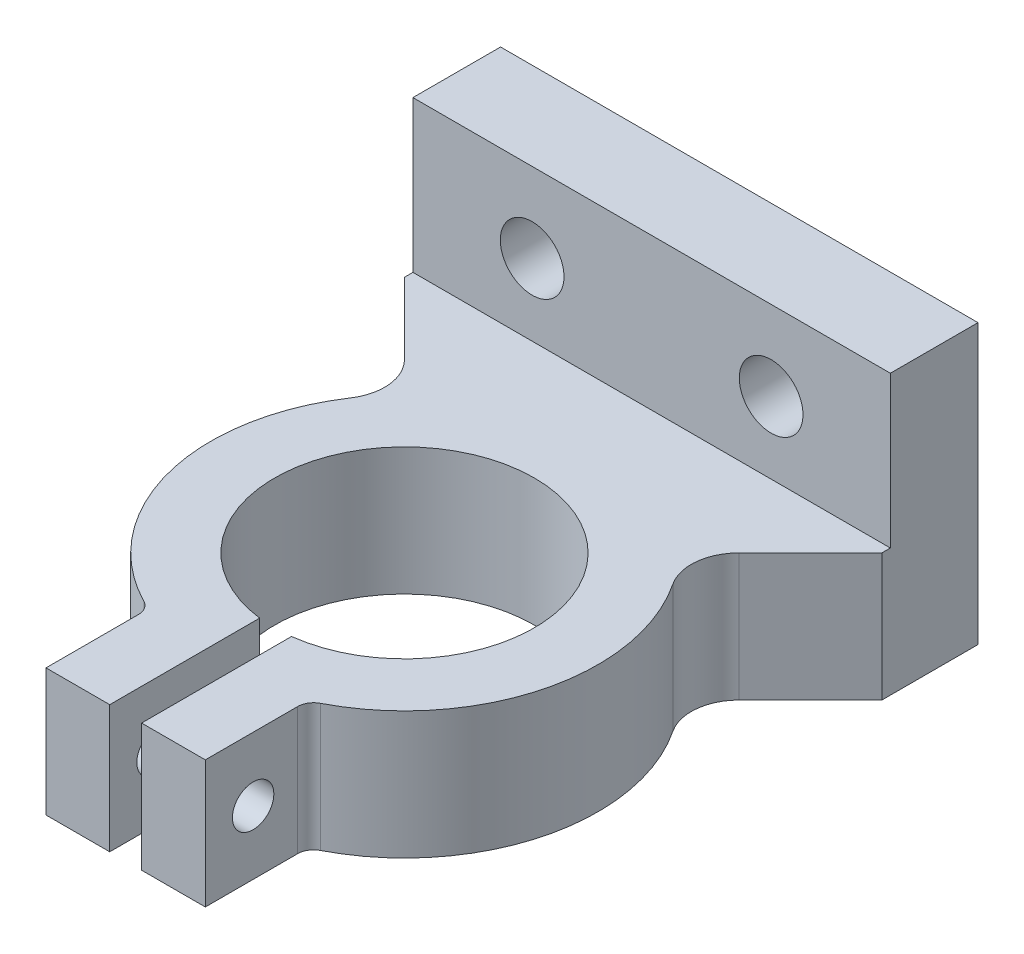
SolidWorks part; units mm, degrees
ref_plane "Front Plane" through (0, 0, 0) normal (0, 0, 1) x (1, 0, 0)
ref_plane "Top Plane" through (0, 0, 0) normal (0, 1, 0) x (1, 0, 0)
ref_plane "Right Plane" through (0, 0, 0) normal (1, 0, 0) x (0, 0, -1)
sketch "Sketch1" plane through (0, 0, 0) normal (0, 1, 0) x (1, 0, 0)
  line L0 (-28.2843, 0) -> (0, 28.2843) construction
  line L1 (-28.2843, 0) -> (0, -28.2843) construction
  line L2 (0, 28.2843) -> (28.2843, 0) construction
  line L3 (0, -28.2843) -> (28.2843, 0) construction
  line L4 (-28.2843, 0) -> (28.2843, 0) construction
  line L5 (0, 28.2843) -> (0, -28.2843) construction
  line L6 (-28.6378, -0.3536) -> (0, -28.9914)
  line L7 (0, -28.9914) -> (28.6378, -0.3536)
  point P1 (0, 0)
  dimension "D1" = 40
  dimension "D2" = 0.5
extrude "Extrude-Thin1" add sketch "Sketch1" along normal blind 60 thin contours L6 L7
sketch "Sketch2" plane through (0, 0, 0) normal (0, 1, 0) x (1, 0, 0)
  line L0 (-31.4663, -3.182) -> (-31.4663, -88)
  line L1 (-31.4663, -88) -> (-2, -88)
  line L2 (31.4663, -88) -> (31.4663, -3.182)
  line L3 (-31.4663, -3.182) -> (0, -34.6482) construction
  line L4 (0, -34.6482) -> (31.4663, -3.182) construction
  line L5 (-31.4663, -3.182) -> (0, -34.6482)
  line L6 (0, -34.6482) -> (31.4663, -3.182)
  line L7 (0, -70) -> (0, -78.5884) construction
  line L8 (-2, -69.1768) -> (-2, -88)
  line L9 (0, -53) -> (0, -34.6482) construction
  line L11 (2, -69.1768) -> (2, -88)
  line L12 (-2, -69.1768) -> (2, -88) construction
  line L13 (-2, -88) -> (2, -69.1768) construction
  line L14 (2, -88) -> (31.4663, -88)
  arc A1 (2, -69.1768) -> (-2, -69.1768) centre (0, -53) ccw
  dimension "D4" = 16.3
  dimension "D1" = 88
  dimension "D2" = 4
  dimension "D3" = 35
extrude "Boss-Extrude1" add sketch "Sketch2" along normal blind 16
sketch "Sketch3" plane through (17.3241, 0, 17.3241) normal (0.7071, 0, 0.7071) x (0.7071, 0, -0.7071)
  line L0 (0, 50) -> (0, 20) construction
  line L1 (2.75, 50) -> (2.75, 20)
  line L2 (-2.75, 50) -> (-2.75, 20)
  arc A0 (2.75, 50) -> (-2.75, 50) centre (0, 50) ccw
  arc A1 (-2.75, 20) -> (2.75, 20) centre (0, 20) ccw
  point P3 (0, 35)
  dimension "D3" = 2.75
  dimension "D1" = 20
  dimension "D2" = 30
extrude "Cut-Extrude1" cut sketch "Sketch3" against normal through all
mirror "Mirror1" about plane through (0, 0, 0) normal (1, 0, 0) of "Cut-Extrude1"
sketch "Sketch5" plane through (0, 0, 0) normal (0, 1, 0) x (1, 0, 0)
  line L0 (-31.4663, -21.5337) -> (-17.1827, -35.8173)
  line L1 (-31.4663, -3.182) -> (-31.4663, -88) construction
  line L2 (-10, -75.147) -> (-10, -88)
  line L3 (-31.4663, -88) -> (-2, -88) construction
  line L4 (-31.4663, -3.182) -> (0, -34.6482) construction
  line L5 (-2, -88) -> (-2, -69.1768) construction
  line L6 (-10, -88) -> (-31.4663, -88)
  line L7 (-31.4663, -88) -> (-31.4663, -21.5337)
  arc A0 (-17.1827, -35.8173) -> (-10, -75.147) centre (0, -53) ccw
  arc A1 (2, -69.1768) -> (-2, -69.1768) centre (0, -53) ccw construction
  dimension "D1" = 8
  dimension "D2" = 8
extrude "Cut-Extrude2" cut sketch "Sketch5" along normal through all
mirror "Mirror2" about plane through (0, 0, 0) normal (1, 0, 0) of "Cut-Extrude2"
fillet "Fillet2" radius 2 2 edges at (10, 8, 75.147) (-10, 8, 75.147)
sketch "Sketch6" plane through (0, 0, 0) normal (1, 0, 0) x (0, 0, -1)
  line L0 (-88, 16) -> (-88, 0) construction
  circle A0 centre (-82, 8) radius 2.6
  dimension "D3" = 5.2
  dimension "D1" = 8
  dimension "D2" = 6
extrude "Cut-Extrude3" cut sketch "Sketch6" against normal through all both and the other way through all
sketch "Sketch7" plane through (-17.3241, 0, 17.3241) normal (-0.7071, 0, 0.7071) x (0.7071, 0, 0.7071)
  line L0 (24.5, 16) -> (-20, 16) construction
  line L1 (-40.1042, 68.8024) -> (38.3195, 68.8024)
  line L2 (-40.1042, 68.8024) -> (-40.1042, 16)
  line L3 (-40.1042, 16) -> (38.3195, 16)
  line L4 (38.3195, 68.8024) -> (38.3195, 16)
  dimension "D1" = 0
extrude "Cut-Extrude4" cut sketch "Sketch7" against normal through all and the other way through all
sketch "Sketch8" plane through (0, 16, 0) normal (0, 1, 0) x (1, 0, 0)
  line L1 (-25.3301, 9.3905) -> (25.9897, 9.3905)
  line L2 (-25.3301, 9.3905) -> (-25.3301, -30.6607)
  line L3 (-25.3301, -30.6607) -> (25.9897, -30.6607)
  line L4 (25.9897, 9.3905) -> (25.9897, -30.6607)
extrude "Boss-Extrude2" add sketch "Sketch8" against normal blind 16
sketch "Sketch9" plane through (0, 16, 0) normal (0, 1, 0) x (1, 0, 0)
  line L1 (-45.4357, 11.8389) -> (46.3414, 11.8389)
  line L2 (-45.4357, 11.8389) -> (-45.4357, -21.9738)
  line L3 (-45.4357, -21.9738) -> (46.3414, -21.9738)
  line L4 (46.3414, 11.8389) -> (46.3414, -21.9738)
extrude "Cut-Extrude5" cut sketch "Sketch9" against normal through all contours L2 L3 L4 L1
sketch "Sketch12" plane through (0, 0, 21.9738) normal (0, 0, -1) x (-1, 0, 0)
  line L1 (-31.4663, 35) -> (31.4663, 35)
  line L2 (-31.4663, 35) -> (-31.4663, 0)
  line L3 (-31.4663, 0) -> (31.4663, 0)
  line L4 (31.4663, 35) -> (31.4663, 0)
  line L5 (31.0262, 16) -> (-31.0262, 16) construction
  circle A0 centre (-15, 25) radius 4
  circle A1 centre (15, 25) radius 4
  point P6 (0, 35)
  dimension "D2" = 8
  dimension "D1" = 35
  dimension "D3" = 30
  dimension "D4" = 15
  dimension "D5" = 9
  dimension "D6" = 9
extrude "Boss-Extrude5" add sketch "Sketch12" along normal blind 11
sketch "Sketch13" plane through (0, 16, 0) normal (0, 1, 0) x (1, 0, 0)
  line L0 (-31.4663, -10.9738) -> (-31.4663, -21.9738) construction
  line L1 (-29.9663, 9.7462) -> (29.9663, 9.7462)
  line L2 (-29.9663, 9.7462) -> (-29.9663, -112.4878)
  line L3 (-29.9663, -112.4878) -> (29.9663, -112.4878)
  line L4 (29.9663, 9.7462) -> (29.9663, -112.4878)
  line L5 (-80.9085, 31.1558) -> (76.1784, 31.1558)
  line L6 (-80.9085, 31.1558) -> (-80.9085, -138.6275)
  line L7 (-80.9085, -138.6275) -> (76.1784, -138.6275)
  line L8 (76.1784, 31.1558) -> (76.1784, -138.6275)
  line L9 (31.4663, -10.9738) -> (31.4663, -21.9738) construction
  point P10 (31.4663, -16.4738)
  dimension "D1" = 1.5
  dimension "D2" = 1.5
extrude "Cut-Extrude6" cut sketch "Sketch13" against normal through all both and the other way through all
fillet "Fillet6" radius 6 2 edges at (-17.1827, 8, 35.8173) (17.1827, 8, 35.8173)
sketch "Sketch14" plane through (0, 0, 10.9738) normal (0, 0, -1) x (-1, 0, 0)
  line L0 (-29.9663, 0) -> (29.9663, 0) construction
  circle A0 centre (0, 10) radius 1.75
  dimension "D1" = 3.5
  dimension "D2" = 10
extrude "Cut-Extrude7" cut sketch "Sketch14" against normal blind 15
sketch "Sketch15" plane through (0, 16, 0) normal (0, 1, 0) x (1, 0, 0)
  line L0 (25.9897, -27.0103) -> (22.3393, -30.6607)
  line L1 (22.3393, -30.6607) -> (25.9897, -30.6607)
  line L2 (25.9897, -30.6607) -> (25.9897, -27.0103)
  line L3 (0, -66.1059) -> (0, -42.6171) construction
  line L4 (-25.9897, -30.6607) -> (-25.9897, -27.0103)
  line L5 (-22.3393, -30.6607) -> (-25.9897, -30.6607)
  line L6 (-25.9897, -27.0103) -> (-22.3393, -30.6607)
extrude "Cut-Extrude8" cut sketch "Sketch15" against normal blind 30
